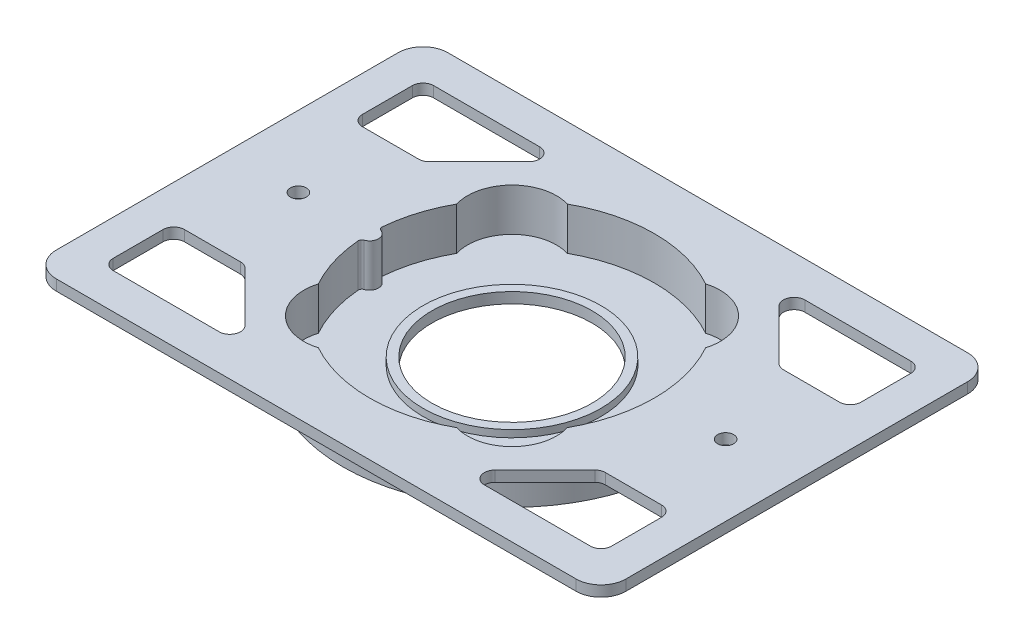
SolidWorks part; units mm, degrees
ref_plane "Front Plane" through (0, 0, 0) normal (0, 0, 1) x (1, 0, 0)
ref_plane "Top Plane" through (0, 0, 0) normal (0, 1, 0) x (1, 0, 0)
ref_plane "Right Plane" through (0, 0, 0) normal (1, 0, 0) x (0, 0, -1)
sketch "Sketch1" plane through (0, 0, 0) normal (0, 1, 0) x (1, 0, 0)
  line L1 (0, 0) -> (160, 0)
  line L2 (0, 0) -> (0, -110)
  line L3 (0, -110) -> (160, -110)
  line L4 (160, 0) -> (160, -110)
  dimension "D1" = 110
  dimension "D2" = 160
extrude "Boss-Extrude1" add sketch "Sketch1" along normal blind 3 contours L2 L3 L4 L1
sketch "Sketch2" plane through (0, 0, 0) normal (0, -1, 0) x (1, 0, 0)
  line L0 (160, 0) -> (0, 110) construction
  line L1 (160, 110) -> (0, 0) construction
  circle A0 centre (80, 55) radius 47.5
  point P8 (80, 55)
  dimension "D3" = 95
extrude "Boss-Extrude3" add sketch "Sketch2" along normal blind 10
fillet "Fillet1" radius 7 1 edges at (160, 1.5, 110)
fillet "Fillet2" radius 7 1 edges at (160, 1.5, 0)
fillet "Fillet3" radius 7 1 edges at (0, 1.5, 0)
fillet "Fillet4" radius 7 1 edges at (0, 1.5, 110)
sketch "Sketch3" plane through (0, 3, 0) normal (0, 1, 0) x (1, 0, 0)
  line L0 (-1000, -55) -> (49000, -55) construction
  line L1 (0, -7) -> (0, -103) construction
  line L2 (80, -1110) -> (80, 48890) construction
  line L3 (7, -110) -> (153, -110) construction
  line L4 (108.2843, -83.2843) -> (51.7157, -26.7157) construction
  line L5 (51.7157, -83.2843) -> (108.2843, -26.7157) construction
  arc A0 (45.0347, -74.4276) -> (60.5724, -89.9653) centre (80, -55) ccw
  arc A1 (60.5724, -20.0347) -> (45.0347, -35.5724) centre (57.019, -32.019) ccw
  arc A2 (114.9653, -35.5724) -> (99.4276, -20.0347) centre (102.981, -32.019) ccw
  arc A3 (99.4276, -89.9653) -> (114.9653, -74.4276) centre (102.981, -77.981) ccw
  arc A4 (45.0347, -74.4276) -> (60.5724, -89.9653) centre (57.019, -77.981) ccw
  arc A5 (99.4276, -89.9653) -> (114.9653, -74.4276) centre (80, -55) ccw
  arc A6 (114.9653, -35.5724) -> (99.4276, -20.0347) centre (80, -55) ccw
  arc A7 (60.5724, -20.0347) -> (45.0347, -35.5724) centre (80, -55) ccw
  point P5 (0, -55)
  point P10 (80, -110)
  dimension "D1" = 80
  dimension "D4" = 25
  dimension "D6" = 25
  dimension "D8" = 25
  dimension "D10" = 25
  dimension "D2" = 45
  dimension "D3" = 45
  dimension "D5" = 32.5
  dimension "D7" = 32.5
  dimension "D9" = 32.5
  dimension "D11" = 32.5
sketch "Sketch8" plane through (0, 3, 0) normal (0, 1, 0) x (1, 0, 0)
  arc A0 (40.1442, -58.3938) -> (40.1442, -51.6062) centre (80, -55) ccw
  circle A1 centre (80, -55) radius 25
  arc A2 (40.8147, -57.3635) -> (40.8147, -52.6365) centre (40, -55) ccw
  arc A3 (40.8147, -52.6365) -> (40.1442, -51.6062) centre (41.1406, -51.6911) cw
  arc A4 (40.1442, -58.3938) -> (40.8147, -57.3635) centre (41.1406, -58.3089) cw
  dimension "D1" = 80
  dimension "D2" = 50
  dimension "D3" = 5
  dimension "D4" = 1
  dimension "D5" = 1
sketch "Sketch9" plane through (0, 3, 0) normal (0, 1, 0) x (1, 0, 0)
  circle A0 centre (80, -55) radius 22.5
  dimension "D1" = 45
sketch "Sketch10" plane through (0, 3, 0) normal (0, 1, 0) x (1, 0, 0)
  circle A0 centre (80, -55) radius 25
  dimension "D1" = 50
extrude "Cut-Extrude3" cut sketch "Sketch3" against normal blind 12
extrude "Cut-Extrude4" cut sketch "Sketch8" against normal blind 12
extrude "Cut-Extrude5" cut sketch "Sketch9" against normal blind 15
sketch "Sketch11" plane through (0, 3, 0) normal (0, 1, 0) x (1, 0, 0)
  line L0 (-920, -55) -> (49080, -55) construction
  line L1 (80, -1000) -> (80, 49000) construction
  line L2 (7, 0) -> (153, 0) construction
  circle A0 centre (20, -55) radius 2.25
  circle A1 centre (140, -55) radius 2.25
  point P10 (80, 0)
  dimension "D1" = 4.5
  dimension "D2" = 60
  dimension "D3" = 4.5
  dimension "D4" = 60
extrude "Cut-Extrude7" cut sketch "Sketch11" against normal blind 9
sketch "Sketch12" plane through (0, 0, 0) normal (0, -1, 0) x (1, 0, 0)
  line L0 (80, -945) -> (80, 49055) construction
  line L1 (23.7528, 55.5) -> (22.3094, 58)
  line L2 (21.4434, 58.5) -> (18.5566, 58.5)
  line L3 (17.6906, 58) -> (16.2472, 55.5)
  line L4 (16.2472, 54.5) -> (17.6906, 52)
  line L5 (18.5566, 51.5) -> (21.4434, 51.5)
  line L6 (22.3094, 52) -> (23.7528, 54.5)
  line L7 (137.6906, 52) -> (136.2472, 54.5)
  line L8 (141.4434, 51.5) -> (138.5566, 51.5)
  line L9 (143.7528, 54.5) -> (142.3094, 52)
  line L10 (142.3094, 58) -> (143.7528, 55.5)
  line L11 (138.5566, 58.5) -> (141.4434, 58.5)
  line L12 (136.2472, 55.5) -> (137.6906, 58)
  circle A0 centre (20, 55) radius 6
  circle A1 centre (20, 55) radius 3.5 construction
  arc A2 (18.5566, 58.5) -> (17.6906, 58) centre (18.5566, 57.5) ccw
  arc A3 (16.2472, 54.5) -> (16.2472, 55.5) centre (17.1132, 55) cw
  arc A4 (18.5566, 51.5) -> (17.6906, 52) centre (18.5566, 52.5) cw
  arc A5 (22.3094, 52) -> (21.4434, 51.5) centre (21.4434, 52.5) cw
  arc A6 (23.7528, 55.5) -> (23.7528, 54.5) centre (22.8868, 55) cw
  arc A7 (22.3094, 58) -> (21.4434, 58.5) centre (21.4434, 57.5) ccw
  circle A8 centre (140, 55) radius 3.5 construction
  arc A9 (137.6906, 58) -> (138.5566, 58.5) centre (138.5566, 57.5) cw
  arc A10 (136.2472, 55.5) -> (136.2472, 54.5) centre (137.1132, 55) ccw
  arc A11 (137.6906, 52) -> (138.5566, 51.5) centre (138.5566, 52.5) ccw
  arc A12 (141.4434, 51.5) -> (142.3094, 52) centre (141.4434, 52.5) ccw
  arc A13 (143.7528, 54.5) -> (143.7528, 55.5) centre (142.8868, 55) ccw
  arc A14 (141.4434, 58.5) -> (142.3094, 58) centre (141.4434, 57.5) cw
  circle A15 centre (140, 55) radius 6
  point P15 (15.9585, 55)
  point P47 (144.0415, 55)
  dimension "D1" = 12
  dimension "D3" = 1
  dimension "D4" = 1
  dimension "D5" = 1
  dimension "D6" = 1
  dimension "D7" = 1
  dimension "D8" = 1
  dimension "D2" = 7
extrude "Boss-Extrude4" add sketch "Sketch12" along normal blind 2
sketch "Sketch13" plane through (0, 3, 0) normal (0, 1, 0) x (1, 0, 0)
  line L0 (-920, -55) -> (49080, -55) construction
  line L1 (80, -1000) -> (80, 49000) construction
  line L2 (7, 0) -> (153, 0) construction
  line L3 (10, -13) -> (10, -27)
  line L4 (0, -7) -> (0, -103) construction
  line L5 (13, -10) -> (42.7574, -10)
  line L6 (13, -30) -> (28.7574, -30)
  line L7 (30.8787, -29.1213) -> (44.8787, -15.1213)
  line L8 (129.1213, -29.1213) -> (115.1213, -15.1213)
  line L9 (147, -30) -> (131.2426, -30)
  line L10 (147, -10) -> (117.2426, -10)
  line L11 (150, -13) -> (150, -27)
  line L12 (150, -97) -> (150, -83)
  line L13 (147, -100) -> (117.2426, -100)
  line L14 (147, -80) -> (131.2426, -80)
  line L15 (129.1213, -80.8787) -> (115.1213, -94.8787)
  line L16 (30.8787, -80.8787) -> (44.8787, -94.8787)
  line L17 (13, -80) -> (28.7574, -80)
  line L18 (13, -100) -> (42.7574, -100)
  line L19 (10, -97) -> (10, -83)
  arc A0 (13, -10) -> (10, -13) centre (13, -13) ccw
  arc A1 (42.7574, -10) -> (44.8787, -15.1213) centre (42.7574, -13) cw
  arc A2 (30.8787, -29.1213) -> (28.7574, -30) centre (28.7574, -27) cw
  arc A3 (10, -27) -> (13, -30) centre (13, -27) ccw
  arc A4 (150, -27) -> (147, -30) centre (147, -27) cw
  arc A5 (129.1213, -29.1213) -> (131.2426, -30) centre (131.2426, -27) ccw
  arc A6 (117.2426, -10) -> (115.1213, -15.1213) centre (117.2426, -13) ccw
  arc A7 (147, -10) -> (150, -13) centre (147, -13) cw
  arc A8 (147, -100) -> (150, -97) centre (147, -97) ccw
  arc A9 (117.2426, -100) -> (115.1213, -94.8787) centre (117.2426, -97) cw
  arc A10 (129.1213, -80.8787) -> (131.2426, -80) centre (131.2426, -83) cw
  arc A11 (150, -83) -> (147, -80) centre (147, -83) ccw
  arc A12 (10, -83) -> (13, -80) centre (13, -83) cw
  arc A13 (30.8787, -80.8787) -> (28.7574, -80) centre (28.7574, -83) ccw
  arc A14 (42.7574, -100) -> (44.8787, -94.8787) centre (42.7574, -97) ccw
  arc A15 (13, -100) -> (10, -97) centre (13, -97) cw
  point P8 (80, 0)
  point P16 (10, -10)
  point P19 (50, -10)
  point P22 (30, -30)
  point P25 (10, -30)
  point P38 (150, -30)
  point P39 (130, -30)
  point P40 (110, -10)
  point P41 (150, -10)
  point P66 (150, -100)
  point P67 (110, -100)
  point P68 (130, -80)
  point P69 (150, -80)
  point P70 (10, -80)
  point P71 (30, -80)
  point P72 (50, -100)
  point P73 (10, -100)
  dimension "D6" = 3
  dimension "D7" = 3
  dimension "D8" = 3
  dimension "D9" = 3
  dimension "D1" = 10
  dimension "D2" = 10
  dimension "D3" = 20
  dimension "D4" = 40
  dimension "D5" = 20
extrude "Cut-Extrude8" cut sketch "Sketch13" against normal blind 10
extrude "Cut-Extrude9" cut sketch "Sketch10" against normal blind 10
